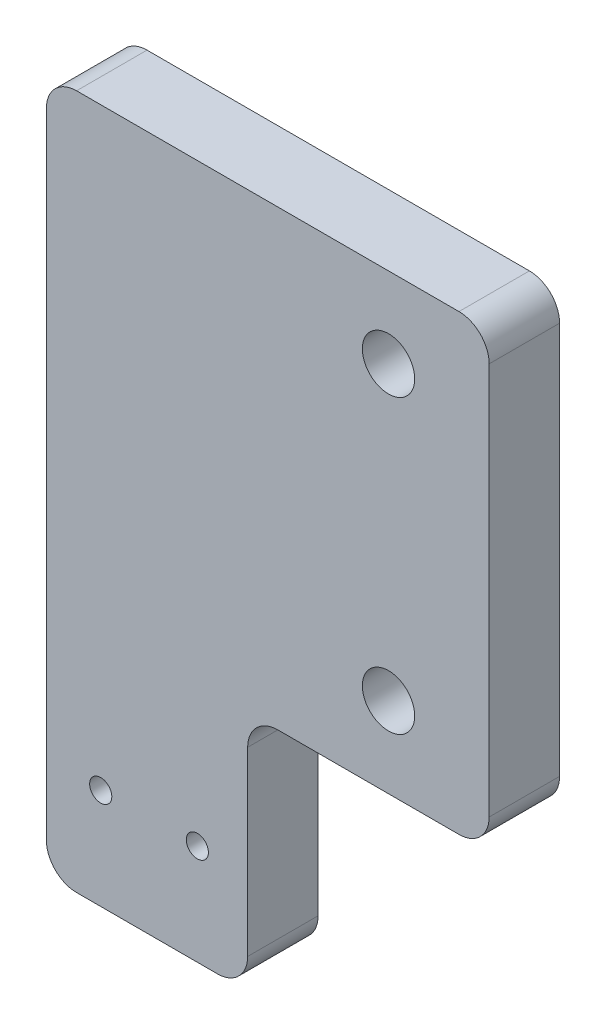
SolidWorks part; units mm, degrees
material "ABS"
ref_plane "Front Plane" through (0, 0, 0) normal (0, 0, 1) x (1, 0, 0)
ref_plane "Top Plane" through (0, 0, 0) normal (0, 1, 0) x (1, 0, 0)
ref_plane "Right Plane" through (0, 0, 0) normal (1, 0, 0) x (0, 0, -1)
sketch "Model" plane through (0, 0, 0) normal (0, 0, 1) x (1, 0, 0)
  line L150 (3, 0) -> (41, 0)
  line L168 (44, -3) -> (44, -42)
  line L239 (20, -48) -> (20, -66)
  line L268 (3, -69) -> (17, -69)
  line L269 (0, -66) -> (0, -3)
  line L270 (41, -45) -> (23, -45)
  arc A0 (3, 0) -> (0, -3) centre (3, -3) ccw
  arc A1 (44, -42) -> (41, -45) centre (41, -42) cw
  arc A2 (23, -45) -> (20, -48) centre (23, -48) ccw
  arc A3 (20, -66) -> (17, -69) centre (17, -66) cw
  arc A4 (0, -66) -> (3, -69) centre (3, -66) ccw
  arc A5 (41, 0) -> (44, -3) centre (41, -3) cw
  circle A6 centre (34, -8) radius 2.6
  circle A7 centre (34, -37) radius 2.6
  circle A8 centre (5.4, -59) radius 1.1
  circle A9 centre (15, -59) radius 1.1
  dimension "D4" = 3
  dimension "D5" = 3
  dimension "D6" = 3
  dimension "D8" = 5.2
  dimension "D9" = 8
  dimension "D10" = 29
  dimension "D11" = 34
  dimension "D12" = 2.2
  dimension "D13" = 5.4
  dimension "D14" = 10
  dimension "D15" = 9.6
  dimension "D1" = 44
  dimension "D2" = 45
  dimension "D3" = 24
  dimension "D7" = 24
extrude "Boss-Extrude1" add sketch "Model" along normal blind 7
